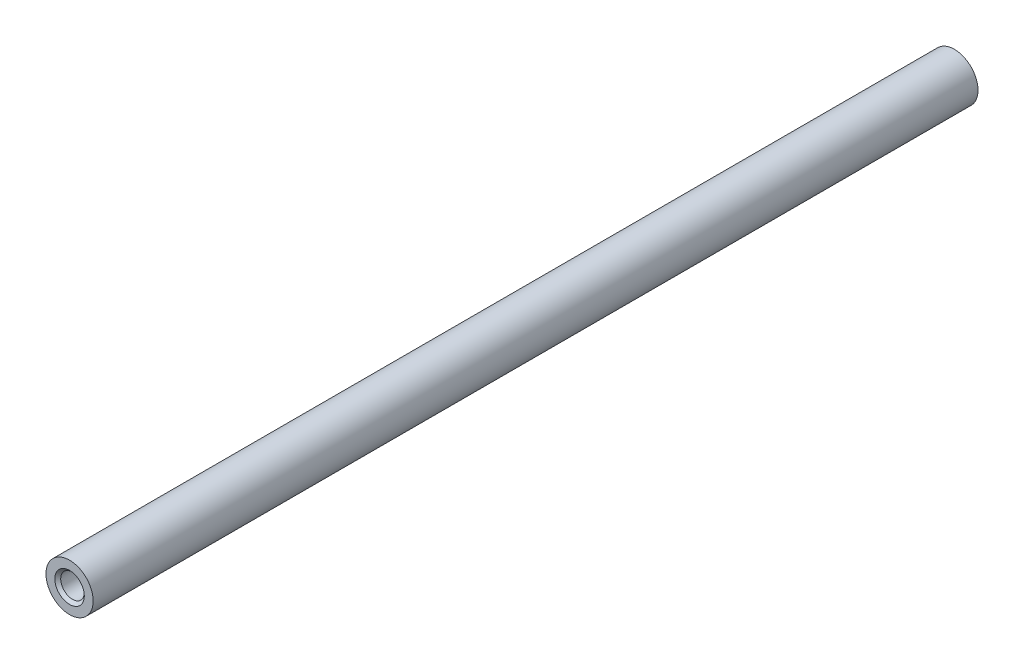
SolidWorks part; units mm, degrees
material "1.0545 (S355N)"
ref_plane "Płaszczyzna przednia" through (0, 0, 0) normal (0, 0, 1) x (1, 0, 0)
ref_plane "Płaszczyzna górna" through (0, 0, 0) normal (0, 1, 0) x (1, 0, 0)
ref_plane "Płaszczyzna prawa" through (0, 0, 0) normal (1, 0, 0) x (0, 0, -1)
sketch "Szkic1" plane through (0, 0, 0) normal (0, 0, 1) x (1, 0, 0)
  circle A0 centre (0, 0) radius 8
  circle A1 centre (0, 0) radius 4
  dimension "D1" = 4
  dimension "D2" = 16
extrude "Dodanie-wyciągnięcie1" add sketch "Szkic1" along normal mid plane 300
sketch "Szkic2" plane through (0, 0, -150) normal (0, 0, -1) x (-1, 0, 0)
  circle A0 centre (0, 0) radius 5
  circle A1 centre (0, 0) radius 4 construction
  dimension "D1" = 1
extrude "Wytnij-wyciągnięcie1" cut sketch "Szkic2" against normal blind 30
chamfer "Sfazowanie1" distance 1 angle 45 1 edges at (4, 0, 150)
